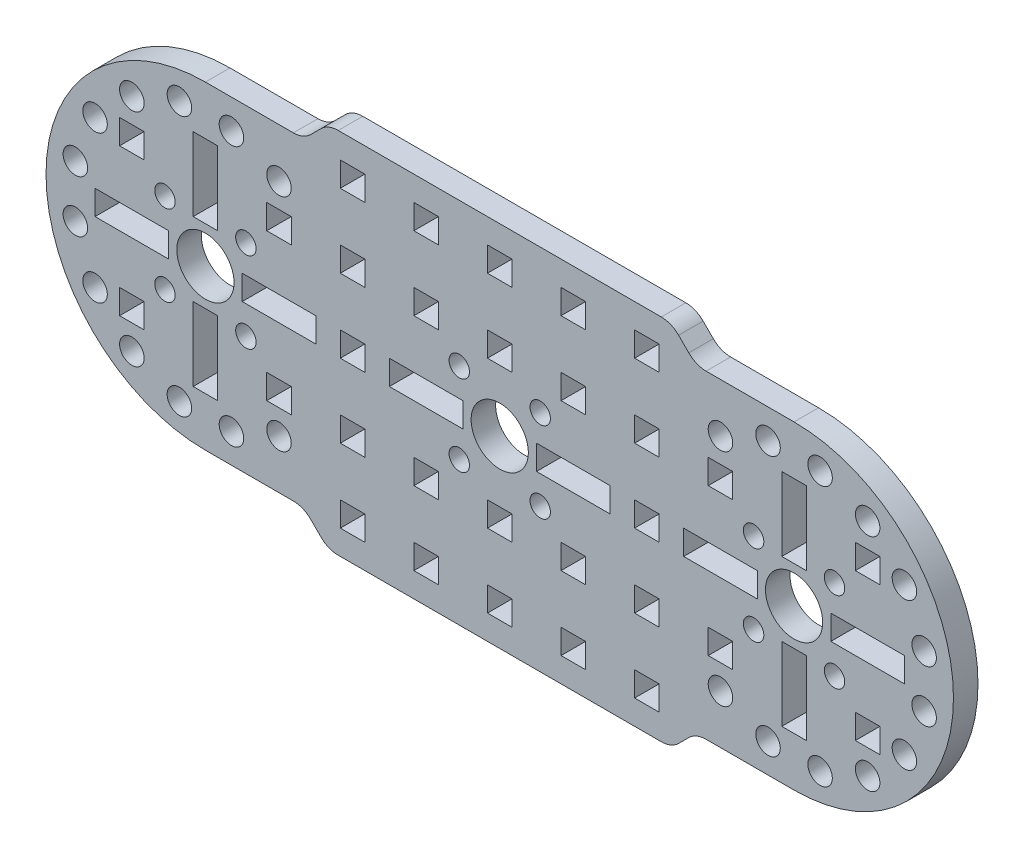
SolidWorks part; units mm, degrees
ref_plane "Alzado" through (0, 0, 0) normal (0, 0, 1) x (1, 0, 0)
ref_plane "Planta" through (0, 0, 0) normal (0, 1, 0) x (1, 0, 0)
ref_plane "Vista lateral" through (0, 0, 0) normal (1, 0, 0) x (0, 0, -1)
sketch "Model" plane through (0, 0, 0) normal (0, 0, 1) x (1, 0, 0)
  line L0 (31.8977, 276.6454) -> (40.8977, 276.6454)
  line L1 (31.8977, 279.6454) -> (31.8977, 276.6454)
  line L2 (40.8977, 279.6454) -> (31.8977, 279.6454)
  line L3 (40.8977, 276.6454) -> (40.8977, 279.6454)
  line L4 (28.8977, 282.6454) -> (28.8977, 291.6454)
  line L5 (25.8977, 282.6454) -> (28.8977, 282.6454)
  line L6 (25.8977, 291.6454) -> (25.8977, 282.6454)
  line L7 (28.8977, 291.6454) -> (25.8977, 291.6454)
  line L8 (22.8977, 279.6454) -> (13.8977, 279.6454)
  line L9 (22.8977, 276.6454) -> (22.8977, 279.6454)
  line L10 (13.8977, 276.6454) -> (22.8977, 276.6454)
  line L11 (13.8977, 279.6454) -> (13.8977, 276.6454)
  line L12 (25.8977, 273.6454) -> (25.8977, 264.6454)
  line L13 (28.8977, 273.6454) -> (25.8977, 273.6454)
  line L14 (28.8977, 264.6454) -> (28.8977, 273.6454)
  line L15 (25.8977, 264.6454) -> (28.8977, 264.6454)
  line L16 (103.8977, 276.6454) -> (112.8977, 276.6454)
  line L17 (103.8977, 279.6454) -> (103.8977, 276.6454)
  line L18 (112.8977, 279.6454) -> (103.8977, 279.6454)
  line L19 (112.8977, 276.6454) -> (112.8977, 279.6454)
  line L20 (100.8977, 282.6454) -> (100.8977, 291.6454)
  line L21 (97.8977, 282.6454) -> (100.8977, 282.6454)
  line L22 (97.8977, 291.6454) -> (97.8977, 282.6454)
  line L23 (100.8977, 291.6454) -> (97.8977, 291.6454)
  line L24 (94.8977, 279.6454) -> (85.8977, 279.6454)
  line L25 (94.8977, 276.6454) -> (94.8977, 279.6454)
  line L26 (85.8977, 276.6454) -> (94.8977, 276.6454)
  line L27 (85.8977, 279.6454) -> (85.8977, 276.6454)
  line L28 (97.8977, 273.6454) -> (97.8977, 264.6454)
  line L29 (100.8977, 273.6454) -> (97.8977, 273.6454)
  line L30 (100.8977, 264.6454) -> (100.8977, 273.6454)
  line L31 (97.8977, 264.6454) -> (100.8977, 264.6454)
  line L32 (67.8977, 276.6454) -> (76.8977, 276.6454)
  line L33 (67.8977, 279.6454) -> (67.8977, 276.6454)
  line L34 (76.8977, 279.6454) -> (67.8977, 279.6454)
  line L35 (76.8977, 276.6454) -> (76.8977, 279.6454)
  line L36 (58.8977, 279.6454) -> (49.8977, 279.6454)
  line L37 (58.8977, 276.6454) -> (58.8977, 279.6454)
  line L38 (49.8977, 276.6454) -> (58.8977, 276.6454)
  line L39 (49.8977, 279.6454) -> (49.8977, 276.6454)
  line L40 (16.8977, 288.6454) -> (16.8977, 285.6454)
  line L41 (19.8977, 288.6454) -> (16.8977, 288.6454)
  line L42 (19.8977, 285.6454) -> (19.8977, 288.6454)
  line L43 (16.8977, 285.6454) -> (19.8977, 285.6454)
  line L44 (34.8977, 270.6454) -> (34.8977, 267.6454)
  line L45 (37.8977, 270.6454) -> (34.8977, 270.6454)
  line L46 (37.8977, 267.6454) -> (37.8977, 270.6454)
  line L47 (34.8977, 267.6454) -> (37.8977, 267.6454)
  line L48 (88.8977, 288.6454) -> (88.8977, 285.6454)
  line L49 (91.8977, 288.6454) -> (88.8977, 288.6454)
  line L50 (91.8977, 285.6454) -> (91.8977, 288.6454)
  line L51 (88.8977, 285.6454) -> (91.8977, 285.6454)
  line L52 (34.8977, 288.6454) -> (34.8977, 285.6454)
  line L53 (37.8977, 288.6454) -> (34.8977, 288.6454)
  line L54 (37.8977, 285.6454) -> (37.8977, 288.6454)
  line L55 (34.8977, 285.6454) -> (37.8977, 285.6454)
  line L56 (43.8977, 261.6454) -> (43.8977, 258.6454)
  line L57 (46.8977, 261.6454) -> (43.8977, 261.6454)
  line L58 (46.8977, 258.6454) -> (46.8977, 261.6454)
  line L59 (43.8977, 258.6454) -> (46.8977, 258.6454)
  line L60 (79.8977, 261.6454) -> (79.8977, 258.6454)
  line L61 (82.8977, 261.6454) -> (79.8977, 261.6454)
  line L62 (82.8977, 258.6454) -> (82.8977, 261.6454)
  line L63 (79.8977, 258.6454) -> (82.8977, 258.6454)
  line L64 (16.8977, 270.6454) -> (16.8977, 267.6454)
  line L65 (19.8977, 270.6454) -> (16.8977, 270.6454)
  line L66 (19.8977, 267.6454) -> (19.8977, 270.6454)
  line L67 (16.8977, 267.6454) -> (19.8977, 267.6454)
  line L68 (43.8977, 279.6454) -> (43.8977, 276.6454)
  line L69 (46.8977, 279.6454) -> (43.8977, 279.6454)
  line L70 (46.8977, 276.6454) -> (46.8977, 279.6454)
  line L71 (43.8977, 276.6454) -> (46.8977, 276.6454)
  line L72 (106.8977, 288.6454) -> (106.8977, 285.6454)
  line L73 (109.8977, 288.6454) -> (106.8977, 288.6454)
  line L74 (109.8977, 285.6454) -> (109.8977, 288.6454)
  line L75 (106.8977, 285.6454) -> (109.8977, 285.6454)
  line L76 (88.8977, 270.6454) -> (88.8977, 267.6454)
  line L77 (91.8977, 270.6454) -> (88.8977, 270.6454)
  line L78 (91.8977, 267.6454) -> (91.8977, 270.6454)
  line L79 (88.8977, 267.6454) -> (91.8977, 267.6454)
  line L80 (79.8977, 279.6454) -> (79.8977, 276.6454)
  line L81 (82.8977, 279.6454) -> (79.8977, 279.6454)
  line L82 (82.8977, 276.6454) -> (82.8977, 279.6454)
  line L83 (79.8977, 276.6454) -> (82.8977, 276.6454)
  line L84 (106.8977, 270.6454) -> (106.8977, 267.6454)
  line L85 (109.8977, 270.6454) -> (106.8977, 270.6454)
  line L86 (109.8977, 267.6454) -> (109.8977, 270.6454)
  line L87 (106.8977, 267.6454) -> (109.8977, 267.6454)
  line L88 (52.8977, 261.6454) -> (52.8977, 258.6454)
  line L89 (55.8977, 261.6454) -> (52.8977, 261.6454)
  line L90 (55.8977, 258.6454) -> (55.8977, 261.6454)
  line L91 (52.8977, 258.6454) -> (55.8977, 258.6454)
  line L92 (61.8977, 261.6454) -> (61.8977, 258.6454)
  line L93 (64.8977, 261.6454) -> (61.8977, 261.6454)
  line L94 (64.8977, 258.6454) -> (64.8977, 261.6454)
  line L95 (61.8977, 258.6454) -> (64.8977, 258.6454)
  line L96 (70.8977, 261.6454) -> (70.8977, 258.6454)
  line L97 (73.8977, 261.6454) -> (70.8977, 261.6454)
  line L98 (73.8977, 258.6454) -> (73.8977, 261.6454)
  line L99 (70.8977, 258.6454) -> (73.8977, 258.6454)
  line L100 (43.8977, 270.6454) -> (43.8977, 267.6454)
  line L101 (46.8977, 270.6454) -> (43.8977, 270.6454)
  line L102 (46.8977, 267.6454) -> (46.8977, 270.6454)
  line L103 (43.8977, 267.6454) -> (46.8977, 267.6454)
  line L104 (79.8977, 270.6454) -> (79.8977, 267.6454)
  line L105 (82.8977, 270.6454) -> (79.8977, 270.6454)
  line L106 (82.8977, 267.6454) -> (82.8977, 270.6454)
  line L107 (79.8977, 267.6454) -> (82.8977, 267.6454)
  line L108 (52.8977, 270.6454) -> (52.8977, 267.6454)
  line L109 (55.8977, 270.6454) -> (52.8977, 270.6454)
  line L110 (55.8977, 267.6454) -> (55.8977, 270.6454)
  line L111 (52.8977, 267.6454) -> (55.8977, 267.6454)
  line L112 (61.8977, 270.6454) -> (61.8977, 267.6454)
  line L113 (64.8977, 270.6454) -> (61.8977, 270.6454)
  line L114 (64.8977, 267.6454) -> (64.8977, 270.6454)
  line L115 (61.8977, 267.6454) -> (64.8977, 267.6454)
  line L116 (70.8977, 270.6454) -> (70.8977, 267.6454)
  line L117 (73.8977, 270.6454) -> (70.8977, 270.6454)
  line L118 (73.8977, 267.6454) -> (73.8977, 270.6454)
  line L119 (70.8977, 267.6454) -> (73.8977, 267.6454)
  line L120 (43.8977, 288.6454) -> (43.8977, 285.6454)
  line L121 (46.8977, 288.6454) -> (43.8977, 288.6454)
  line L122 (46.8977, 285.6454) -> (46.8977, 288.6454)
  line L123 (43.8977, 285.6454) -> (46.8977, 285.6454)
  line L124 (79.8977, 288.6454) -> (79.8977, 285.6454)
  line L125 (82.8977, 288.6454) -> (79.8977, 288.6454)
  line L126 (82.8977, 285.6454) -> (82.8977, 288.6454)
  line L127 (79.8977, 285.6454) -> (82.8977, 285.6454)
  line L128 (52.8977, 288.6454) -> (52.8977, 285.6454)
  line L129 (55.8977, 288.6454) -> (52.8977, 288.6454)
  line L130 (55.8977, 285.6454) -> (55.8977, 288.6454)
  line L131 (52.8977, 285.6454) -> (55.8977, 285.6454)
  line L132 (61.8977, 288.6454) -> (61.8977, 285.6454)
  line L133 (64.8977, 288.6454) -> (61.8977, 288.6454)
  line L134 (64.8977, 285.6454) -> (64.8977, 288.6454)
  line L135 (61.8977, 285.6454) -> (64.8977, 285.6454)
  line L136 (70.8977, 288.6454) -> (70.8977, 285.6454)
  line L137 (73.8977, 288.6454) -> (70.8977, 288.6454)
  line L138 (73.8977, 285.6454) -> (73.8977, 288.6454)
  line L139 (70.8977, 285.6454) -> (73.8977, 285.6454)
  line L140 (43.8977, 297.6454) -> (43.8977, 294.6454)
  line L141 (46.8977, 297.6454) -> (43.8977, 297.6454)
  line L142 (46.8977, 294.6454) -> (46.8977, 297.6454)
  line L143 (43.8977, 294.6454) -> (46.8977, 294.6454)
  line L144 (79.8977, 297.6454) -> (79.8977, 294.6454)
  line L145 (82.8977, 297.6454) -> (79.8977, 297.6454)
  line L146 (82.8977, 294.6454) -> (82.8977, 297.6454)
  line L147 (79.8977, 294.6454) -> (82.8977, 294.6454)
  line L148 (52.8977, 297.6454) -> (52.8977, 294.6454)
  line L149 (55.8977, 297.6454) -> (52.8977, 297.6454)
  line L150 (55.8977, 294.6454) -> (55.8977, 297.6454)
  line L151 (52.8977, 294.6454) -> (55.8977, 294.6454)
  line L152 (61.8977, 297.6454) -> (61.8977, 294.6454)
  line L153 (64.8977, 297.6454) -> (61.8977, 297.6454)
  line L154 (64.8977, 294.6454) -> (64.8977, 297.6454)
  line L155 (61.8977, 294.6454) -> (64.8977, 294.6454)
  line L156 (70.8977, 297.6454) -> (70.8977, 294.6454)
  line L157 (73.8977, 297.6454) -> (70.8977, 297.6454)
  line L158 (73.8977, 294.6454) -> (73.8977, 297.6454)
  line L159 (70.8977, 294.6454) -> (73.8977, 294.6454)
  line L160 (43.6403, 300.6454) -> (83.155, 300.6454)
  line L162 (27.3977, 297.6454) -> (38.155, 297.6454)
  line L163 (99.3977, 297.6454) -> (88.6403, 297.6454)
  line L164 (40.2763, 298.524) -> (41.519, 299.7667)
  line L165 (86.519, 298.524) -> (85.2763, 299.7667)
  line L166 (43.6403, 255.6454) -> (83.155, 255.6454)
  line L168 (27.3977, 258.6454) -> (38.155, 258.6454)
  line L169 (99.3977, 258.6454) -> (88.6403, 258.6454)
  line L170 (40.2763, 257.7667) -> (41.519, 256.524)
  line L171 (86.519, 257.7667) -> (85.2763, 256.524)
  circle A0 centre (22.4479, 283.0951) radius 1.25
  circle A1 centre (22.4479, 273.1956) radius 1.25
  circle A2 centre (32.3474, 273.1956) radius 1.25
  circle A3 centre (32.3474, 283.0951) radius 1.25
  circle A4 centre (27.3977, 278.1454) radius 3.5
  circle A5 centre (18.3977, 291.6454) radius 1.5
  circle A6 centre (18.3977, 264.6454) radius 1.5
  circle A7 centre (36.3977, 291.6454) radius 1.5
  circle A8 centre (36.3977, 264.6454) radius 1.5
  circle A9 centre (13.8977, 269.1454) radius 1.5
  circle A10 centre (13.8977, 287.1454) radius 1.5
  circle A11 centre (30.5796, 294.0553) radius 1.5
  circle A12 centre (24.2157, 262.2355) radius 1.5
  circle A13 centre (30.5796, 262.2355) radius 1.5
  circle A14 centre (24.2157, 294.0553) radius 1.5
  circle A15 centre (11.4878, 281.3273) radius 1.5
  circle A16 centre (11.4878, 274.9634) radius 1.5
  circle A17 centre (94.4479, 283.0951) radius 1.25
  circle A18 centre (94.4479, 273.1956) radius 1.25
  circle A19 centre (104.3474, 273.1956) radius 1.25
  circle A20 centre (104.3474, 283.0951) radius 1.25
  circle A21 centre (99.3977, 278.1454) radius 3.5
  circle A22 centre (90.3977, 291.6454) radius 1.5
  circle A23 centre (90.3977, 264.6454) radius 1.5
  circle A24 centre (108.3977, 291.6454) radius 1.5
  circle A25 centre (108.3977, 264.6454) radius 1.5
  circle A26 centre (112.8977, 269.1454) radius 1.5
  circle A27 centre (112.8977, 287.1454) radius 1.5
  circle A28 centre (102.5796, 294.0553) radius 1.5
  circle A29 centre (96.2157, 262.2355) radius 1.5
  circle A30 centre (102.5796, 262.2355) radius 1.5
  circle A31 centre (96.2157, 294.0553) radius 1.5
  circle A32 centre (115.3076, 274.9634) radius 1.5
  circle A33 centre (115.3076, 281.3273) radius 1.5
  circle A34 centre (58.4479, 283.0951) radius 1.25
  circle A35 centre (58.4479, 273.1956) radius 1.25
  circle A36 centre (68.3474, 273.1956) radius 1.25
  circle A37 centre (68.3474, 283.0951) radius 1.25
  circle A38 centre (63.3977, 278.1454) radius 3.5
  arc A39 (27.3977, 297.6454) -> (27.3977, 258.6454) centre (27.3977, 278.1454) ccw
  arc A40 (38.155, 297.6454) -> (40.2763, 298.524) centre (38.155, 300.6454) ccw
  arc A41 (86.519, 298.524) -> (88.6403, 297.6454) centre (88.6403, 300.6454) ccw
  arc A42 (99.3977, 258.6454) -> (99.3977, 297.6454) centre (99.3977, 278.1454) ccw
  arc A43 (43.6403, 300.6454) -> (41.519, 299.7667) centre (43.6403, 297.6454) ccw
  arc A44 (85.2763, 299.7667) -> (83.155, 300.6454) centre (83.155, 297.6454) ccw
  arc A45 (40.2763, 257.7667) -> (38.155, 258.6454) centre (38.155, 255.6454) ccw
  arc A46 (88.6403, 258.6454) -> (86.519, 257.7667) centre (88.6403, 255.6454) ccw
  arc A47 (41.519, 256.524) -> (43.6403, 255.6454) centre (43.6403, 258.6454) ccw
  arc A48 (83.155, 255.6454) -> (85.2763, 256.524) centre (83.155, 258.6454) ccw
extrude "Saliente-Extruir1" add sketch "Model" along normal blind 3
